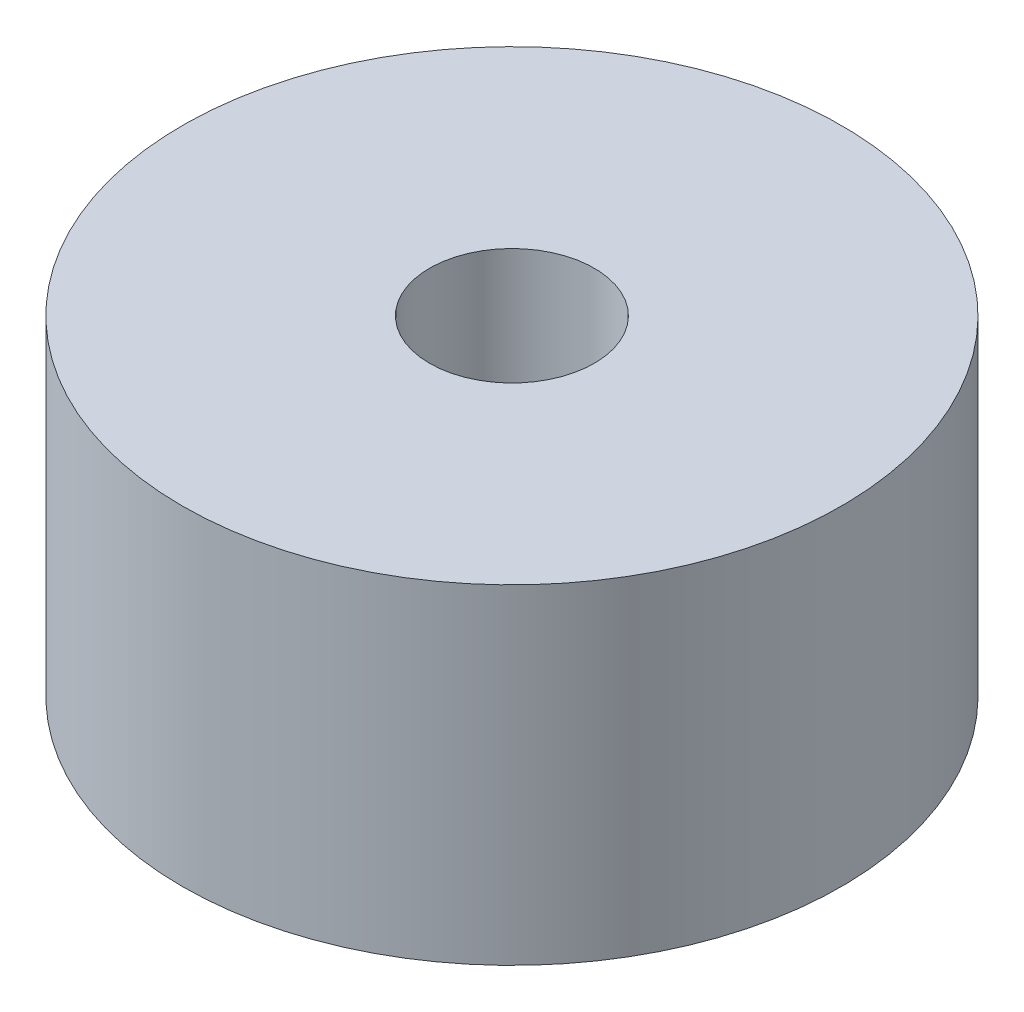
SolidWorks part; units mm, degrees
ref_plane "Front Plane" through (0, 0, 0) normal (0, 0, 1) x (1, 0, 0)
ref_plane "Top Plane" through (0, 0, 0) normal (0, 1, 0) x (1, 0, 0)
ref_plane "Right Plane" through (0, 0, 0) normal (1, 0, 0) x (0, 0, -1)
sketch "Sketch1" plane through (0, 0, 0) normal (0, 1, 0) x (1, 0, 0)
  circle A0 centre (0, 0) radius 3.175
  circle A1 centre (0, 0) radius 12.7
  dimension "D1" = 25.4
  dimension "D2" = 6.35
extrude "Boss-Extrude1" add sketch "Sketch1" along normal blind 12.7
